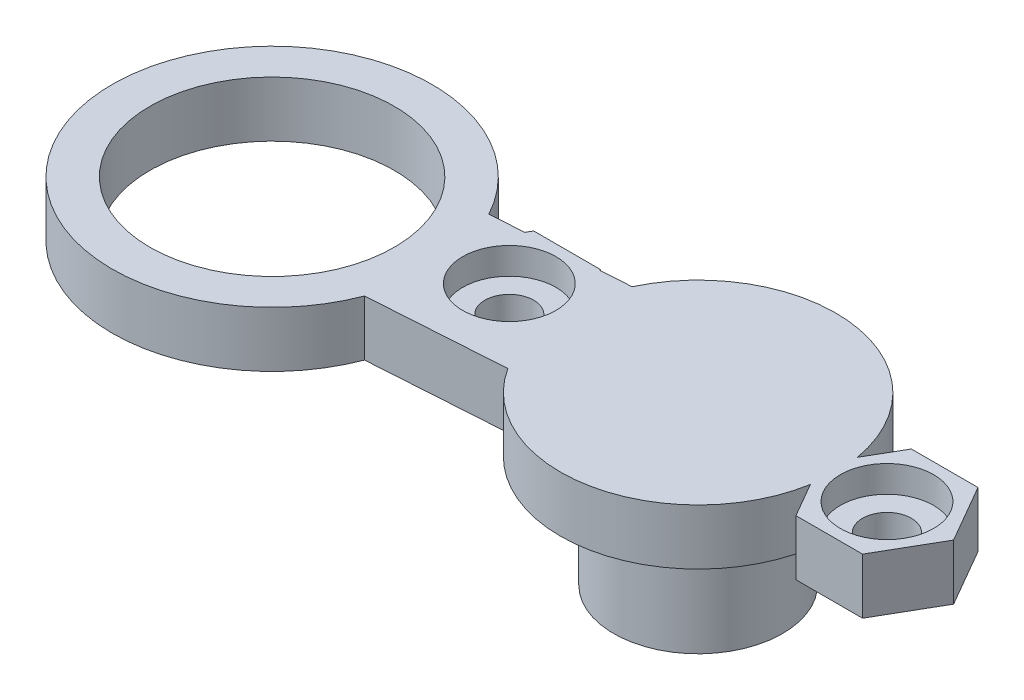
SolidWorks part; units mm, degrees
other "Compression Link 3 Moving Ball Retainer"
other "Compression Link 3 Moving Ball Retainer Left"
ref_plane "Front Plane" through (0, 0, 0) normal (0, 0, 1) x (1, 0, 0)
ref_plane "Top Plane" through (0, 0, 0) normal (0, 1, 0) x (1, 0, 0)
ref_plane "Right Plane" through (0, 0, 0) normal (1, 0, 0) x (0, 0, -1)
sketch3d "Retainer Feature 1 profile datum points"
  point P0 (-56.2917, -101, 30)
  point P1 (-46.2917, -101, 30)
  point P2 (-56.2917, -101, 40)
ref_plane "Retainer Feature 1 profile plane" through (0, -101, 0) normal (0, -1, 0) x (-1, 0, 0)
sketch "Retainer Feature 1 profile" plane through (0, -101, 0) normal (0, -1, 0) x (-1, 0, 0)
  circle A0 centre (56.2917, -30) radius 3.8
extrude "Retainer Feature 1" add sketch "Retainer Feature 1 profile" along normal blind 5.02 separate body
sketch3d "Retainer Feature 2 profile datum points"
  point P0 (-56.2917, -106, 30)
  point P1 (-46.2917, -106, 30)
  point P2 (-56.2917, -106, 40)
ref_plane "Retainer Feature 2 profile plane" through (0, -106, 0) normal (0, -1, 0) x (-1, 0, 0)
sketch "Retainer Feature 2 profile" plane through (0, -106, 0) normal (0, -1, 0) x (-1, 0, 0)
  circle A0 centre (56.2917, -30) radius 6.2
extrude "Retainer Feature 2" add sketch "Retainer Feature 2 profile" along normal blind 2.5
sketch3d "Middle Right Floating Compression Ball Retainer 3 Hexagonal Screw Pad 42 datum points"
  point P0 (-47.7917, -106, 30)
  point P1 (-37.7917, -106, 30)
  point P2 (-47.7917, -106, 40)
ref_plane "Middle Right Floating Compression Ball Retainer 3 Hexagonal Screw Pad 42 plane" through (0, -106, 0) normal (0, -1, 0) x (-1, 0, 0)
sketch "Middle Right Floating Compression Ball Retainer 3 Hexagonal Screw Pad 42" plane through (0, -106, 0) normal (0, -1, 0) x (-1, 0, 0)
  line L0 (44.7917, -30) -> (46.2917, -32.5981)
  line L1 (46.2917, -32.5981) -> (49.2917, -32.5981)
  line L2 (49.2917, -32.5981) -> (50.7917, -30)
  line L3 (50.7917, -30) -> (49.2917, -27.4019)
  line L4 (49.2917, -27.4019) -> (46.2917, -27.4019)
  line L5 (46.2917, -27.4019) -> (44.7917, -30)
extrude "Retainer Feature 5" add sketch "Middle Right Floating Compression Ball Retainer 3 Hexagonal Screw Pad 42" along normal blind 2.5
sketch3d "Middle Right Floating Compression Ball Retainer 3 Hexagonal Screw Pad 45 datum points"
  point P0 (-64.7917, -106, 30)
  point P1 (-54.7917, -106, 30)
  point P2 (-64.7917, -106, 40)
ref_plane "Middle Right Floating Compression Ball Retainer 3 Hexagonal Screw Pad 45 plane" through (0, -106, 0) normal (0, -1, 0) x (-1, 0, 0)
sketch "Middle Right Floating Compression Ball Retainer 3 Hexagonal Screw Pad 45" plane through (0, -106, 0) normal (0, -1, 0) x (-1, 0, 0)
  line L0 (61.7917, -30) -> (63.2917, -32.5981)
  line L1 (63.2917, -32.5981) -> (66.2917, -32.5981)
  line L2 (66.2917, -32.5981) -> (67.7917, -30)
  line L3 (67.7917, -30) -> (66.2917, -27.4019)
  line L4 (66.2917, -27.4019) -> (63.2917, -27.4019)
  line L5 (63.2917, -27.4019) -> (61.7917, -30)
extrude "Retainer Feature 8" add sketch "Middle Right Floating Compression Ball Retainer 3 Hexagonal Screw Pad 45" along normal blind 2.5
sketch3d "Retainer Feature 9 axis line"
  line L0 (-56.2917, -101, 20) -> (-56.2917, -101, 40) construction
ref_axis "Retainer Feature 9 axis" through (-56.2917, -101, 20) along (0, 0, 1)
sketch3d "Retainer Feature 9 profile datum points"
  point P0 (-56.2917, -101, 30)
  point P1 (-46.2917, -101, 30)
  point P2 (-56.2917, -101, 40)
ref_plane "Retainer Feature 9 profile plane" through (0, -101, 0) normal (0, -1, 0) x (-1, 0, 0)
sketch "Retainer Feature 9 profile" plane through (0, -101, 0) normal (0, -1, 0) x (-1, 0, 0)
  line L0 (56.2917, -33.15) -> (56.2917, -26.85)
  arc A0 (56.2917, -26.85) -> (56.2917, -33.15) centre (56.2917, -30) ccw
revolve "Retainer Feature 9" cut sketch "Retainer Feature 9 profile" angle 360 about axis through (-56.2917, -101, 20) along (0, 0, 1)
sketch3d "Middle Right Floating Compression Ball Retainer 3 Plate Sketch 177 datum points"
  point P0 (-56.2917, -106, 30)
  point P1 (-66.2703, -106, 30.6524)
  point P2 (-56.9441, -106, 20.0213)
ref_plane "Middle Right Floating Compression Ball Retainer 3 Plate Sketch 177 plane" through (0, -106, 0) normal (0, -1, 0) x (-1, 0, 0)
sketch "Middle Right Floating Compression Ball Retainer 3 Plate Sketch 177" plane through (0, -106, 0) normal (0, -1, 0) x (-1, 0, 0)
  line L0 (56.0959, -32.9936) -> (74.0959, -34.1705)
  line L1 (74.0959, -34.1705) -> (74.4874, -28.1833)
  line L2 (74.4874, -28.1833) -> (56.4874, -27.0064)
  line L3 (56.4874, -27.0064) -> (56.0959, -32.9936)
extrude "Retainer Feature 12" add sketch "Middle Right Floating Compression Ball Retainer 3 Plate Sketch 177" along normal blind 2.5
sketch3d "Retainer Feature 13 profile datum points"
  point P0 (-74.2917, -106, 31.1769)
  point P1 (-64.2917, -106, 31.1769)
  point P2 (-74.2917, -106, 41.1769)
ref_plane "Retainer Feature 13 profile plane" through (0, -106, 0) normal (0, -1, 0) x (-1, 0, 0)
sketch "Retainer Feature 13 profile" plane through (0, -106, 0) normal (0, -1, 0) x (-1, 0, 0)
  circle A0 centre (74.2917, -31.1769) radius 7.2
extrude "Retainer Feature 13" add sketch "Retainer Feature 13 profile" along normal blind 2.5
sketch3d "Retainer Feature 14 profile datum points"
  point P0 (-74.2917, -105.9, 31.1769)
  point P1 (-64.2917, -105.9, 31.1769)
  point P2 (-74.2917, -105.9, 41.1769)
ref_plane "Retainer Feature 14 profile plane" through (0, -105.9, 0) normal (0, -1, 0) x (-1, 0, 0)
sketch "Retainer Feature 14 profile" plane through (0, -105.9, 0) normal (0, -1, 0) x (-1, 0, 0)
  circle A0 centre (74.2917, -31.1769) radius 5.5
extrude "Retainer Feature 14" cut sketch "Retainer Feature 14 profile" along normal blind 2.7
sketch3d "Retainer Feature 15 profile datum points"
  point P0 (-47.7917, -105, 30)
  point P1 (-37.7917, -105, 30)
  point P2 (-47.7917, -105, 40)
ref_plane "Retainer Feature 15 profile plane" through (0, -105, 0) normal (0, -1, 0) x (-1, 0, 0)
sketch "Retainer Feature 15 profile" plane through (0, -105, 0) normal (0, -1, 0) x (-1, 0, 0)
  circle A0 centre (47.7917, -30) radius 1.1
extrude "Retainer Feature 15" cut sketch "Retainer Feature 15 profile" along normal blind 3.75
sketch3d "Retainer Feature 16 profile datum points"
  point P0 (-47.7917, -107.3, 30)
  point P1 (-37.7917, -107.3, 30)
  point P2 (-47.7917, -107.3, 40)
ref_plane "Retainer Feature 16 profile plane" through (0, -107.3, 0) normal (0, -1, 0) x (-1, 0, 0)
sketch "Retainer Feature 16 profile" plane through (0, -107.3, 0) normal (0, -1, 0) x (-1, 0, 0)
  circle A0 centre (47.7917, -30) radius 2.1
extrude "Retainer Feature 16" cut sketch "Retainer Feature 16 profile" along normal blind 1.45
sketch3d "Retainer Feature 17 profile datum points"
  point P0 (-64.7917, -105, 30)
  point P1 (-54.7917, -105, 30)
  point P2 (-64.7917, -105, 40)
ref_plane "Retainer Feature 17 profile plane" through (0, -105, 0) normal (0, -1, 0) x (-1, 0, 0)
sketch "Retainer Feature 17 profile" plane through (0, -105, 0) normal (0, -1, 0) x (-1, 0, 0)
  circle A0 centre (64.7917, -30) radius 1.1
extrude "Retainer Feature 17" cut sketch "Retainer Feature 17 profile" along normal blind 3.75
sketch3d "Retainer Feature 18 profile datum points"
  point P0 (-64.7917, -107.3, 30)
  point P1 (-54.7917, -107.3, 30)
  point P2 (-64.7917, -107.3, 40)
ref_plane "Retainer Feature 18 profile plane" through (0, -107.3, 0) normal (0, -1, 0) x (-1, 0, 0)
sketch "Retainer Feature 18 profile" plane through (0, -107.3, 0) normal (0, -1, 0) x (-1, 0, 0)
  circle A0 centre (64.7917, -30) radius 2.1
extrude "Retainer Feature 18" cut sketch "Retainer Feature 18 profile" along normal blind 1.45
sketch3d "Articulation Throat axis line"
  line L0 (-53.1481, -106.3831, 37.8192) -> (-59.4352, -95.6169, 22.1808) construction
ref_axis "Articulation Throat axis" through (-53.1481, -106.3831, 37.8192) along (-0.3144, 0.5383, -0.7819)
sketch3d "Articulation Throat Sketch datum points"
  point P0 (-56.2917, -101, 30)
  point P1 (-56.2917, -109.2368, 24.3295)
  point P2 (-59.4352, -95.6169, 22.1808)
ref_plane "Articulation Throat Sketch plane" through (-75.1941, -14.1195, 20.5094) normal (0.9493, 0.1783, -0.2589) x (-0.2545, -0.0478, -0.9659)
sketch "Articulation Throat Sketch" plane through (-75.1941, -14.1195, 20.5094) normal (0.9493, 0.1783, -0.2589) x (-0.2545, -0.0478, -0.9659)
  line L0 (-9.8257, -88.8766) -> (-8.4754, -90.7385)
  line L1 (-8.4754, -90.7385) -> (14.089, -82.6758)
  line L2 (14.089, -82.6758) -> (8.7936, -75.3739)
  line L3 (8.7936, -75.3739) -> (-9.8257, -88.8766)
revolve "Articulation Throat" cut sketch "Articulation Throat Sketch" angle 360 about axis through (-53.1481, -106.3831, 37.8192) along (-0.3144, 0.5383, -0.7819)
sketch3d "Mirror1 profile datum points"
  point P0 (0, 0, 0)
  point P1 (10, 0, 0)
  point P2 (0, 0, 10)
ref_plane "Mirror1 profile plane" through (0, 0, 0) normal (0, -1, 0) x (-1, 0, 0)
mirror "Mirror1" about plane through (0, 0, 0) normal (0, -1, 0) of bodies 113
delete or keep bodies "Remove1" type delete bodies bodies 113
